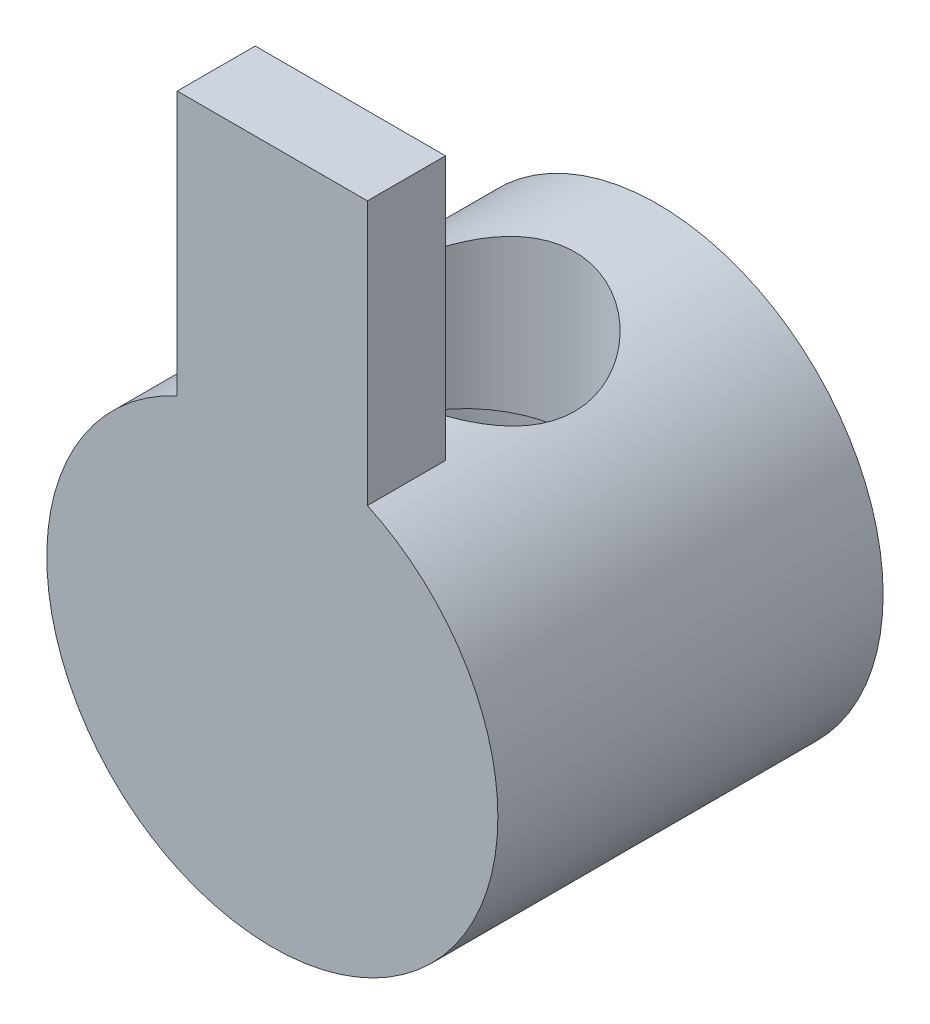
SolidWorks part; units mm, degrees
ref_plane "前视基准面" through (0, 0, 0) normal (0, 0, 1) x (1, 0, 0)
ref_plane "上视基准面" through (0, 0, 0) normal (0, 1, 0) x (1, 0, 0)
ref_plane "右视基准面" through (0, 0, 0) normal (1, 0, 0) x (0, 0, -1)
sketch "草图1" plane through (0, 0, 0) normal (0, 0, 1) x (1, 0, 0)
  line L1 (-3.9, -14.23) -> (3.9, -14.23)
  line L2 (-3.9, -14.23) -> (-3.9, 14.23)
  line L3 (-3.9, 14.23) -> (3.9, 14.23)
  line L4 (3.9, -14.23) -> (3.9, 14.23)
  line L5 (-3.9, -14.23) -> (3.9, 14.23) construction
  line L6 (-3.9, 14.23) -> (3.9, -14.23) construction
  point P0 (0, 0)
  dimension "D1" = 7.8
  dimension "D2" = 28.46
extrude "凸台-拉伸1" add sketch "草图1" along normal blind 3.2
sketch "草图4" plane through (0, 0, 0) normal (0, 0, -1) x (-1, 0, 0)
  line L0 (3.9, 14.23) -> (3.9, -14.23) construction
  line L1 (-3.9, -14.23) -> (3.9, -14.23)
  line L2 (-3.9, -14.23) -> (-3.9, -7.0516)
  line L3 (-3.9, -7.0516) -> (3.9, -7.0516)
  line L4 (3.9, -14.23) -> (3.9, -7.0516)
extrude "切除-拉伸1" cut sketch "草图4" against normal through all
sketch "草图2" plane through (0, 0, 3.2) normal (0, 0, 1) x (1, 0, 0)
  circle A0 centre (0, -4.98) radius 9.25
  dimension "D1" = 18.5
extrude "凸台-拉伸2" add sketch "草图2" against normal blind 15.8
sketch "草图5" plane through (0, 14.23, 0) normal (0, 1, 0) x (1, 0, 0)
  line L0 (0, -3.2) -> (0, 12.6) construction
  line L1 (3.9, -3.2) -> (-3.9, -3.2) construction
  line L2 (9.25, 12.6) -> (-9.25, 12.6) construction
  circle A0 centre (0, 4.7) radius 4.5
  point P8 (0, 4.7)
  dimension "D1" = 9
extrude "切除-拉伸2" cut sketch "草图5" against normal through all
ref_plane "基准面1" through (0, -14.23, 0) normal (0, 1, 0) x (-1, 0, 0)
sketch "草图6" plane through (0, -14.23, 0) normal (0, 1, 0) x (-1, 0, 0)
  circle A0 centre (0, -4.7) radius 6.75
  dimension "D1" = 13.5
extrude "切除-拉伸3" cut sketch "草图6" along normal blind 12
